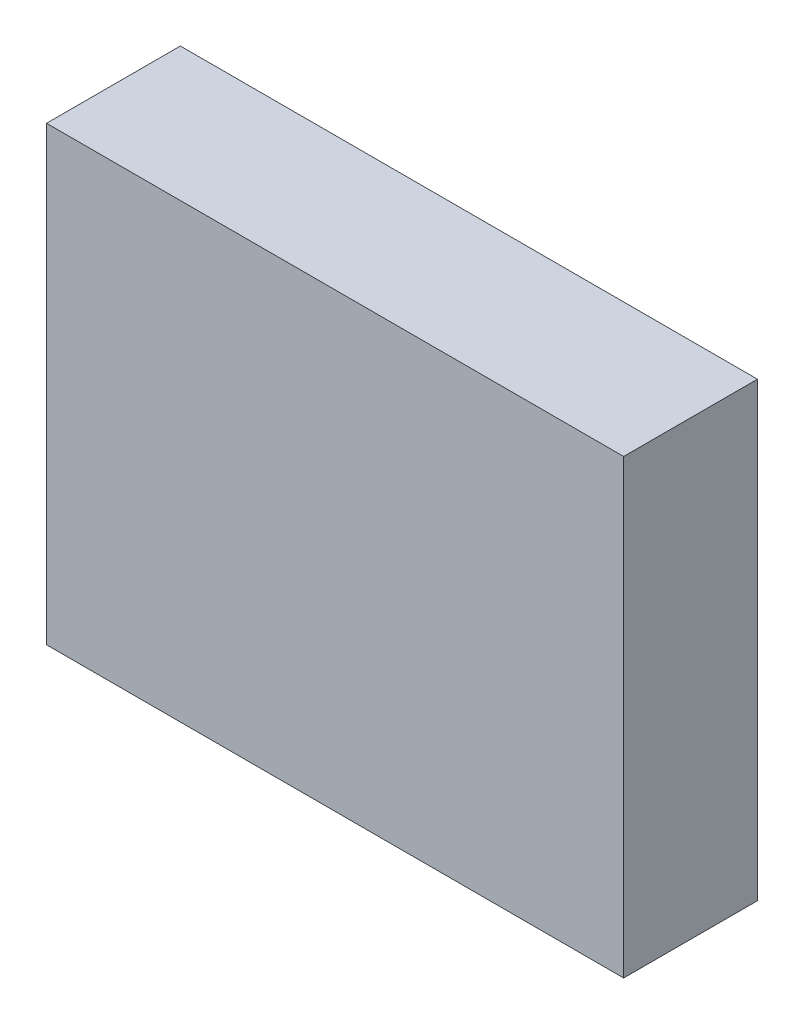
SolidWorks part; units mm, degrees
ref_plane "Front Plane" through (0, 0, 0) normal (0, 0, 1) x (1, 0, 0)
ref_plane "Top Plane" through (0, 0, 0) normal (0, 1, 0) x (1, 0, 0)
ref_plane "Right Plane" through (0, 0, 0) normal (1, 0, 0) x (0, 0, -1)
sketch "Sketch1" plane through (0, 0, 0) normal (0, 0, 1) x (1, 0, 0)
  line L1 (0, 0) -> (69, 0)
  line L2 (0, 0) -> (0, 54)
  line L3 (0, 54) -> (69, 54)
  line L4 (69, 0) -> (69, 54)
  dimension "D1" = 69
  dimension "D2" = 54
extrude "Profile" add sketch "Sketch1" along normal blind 16
equation "\"Profile_Depth\" = 16mm"
equation "\"D1@Profile\" = \"Profile_Depth\""
equation "\"Profile_Sketch_1\" = 69mm"
equation "\"D1@Sketch1\" = \"Profile_Sketch_1\""
equation "\"Profile_Sketch_2\" = 54mm"
equation "\"D2@Sketch1\" = \"Profile_Sketch_2\""
equation "\"EnvelopeWidth\" = 69mm"
equation "\"EnvelopeHeight\" = 54mm"
